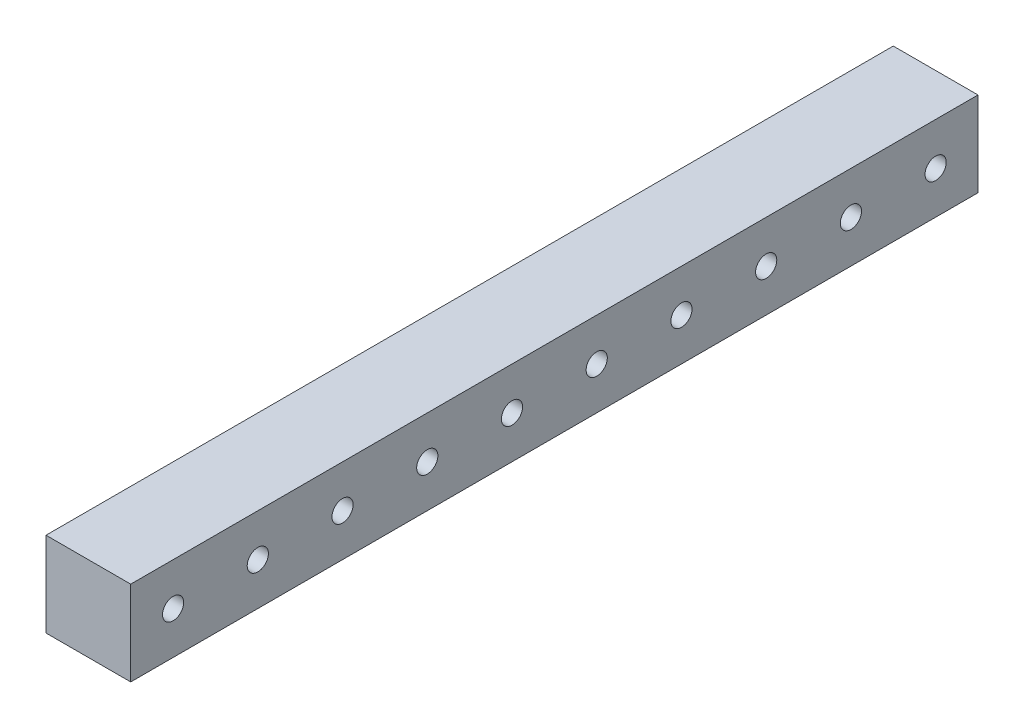
SolidWorks part; units mm, degrees
material "Pine"
ref_plane "Front Plane" through (0, 0, 0) normal (0, 0, 1) x (1, 0, 0)
ref_plane "Top Plane" through (0, 0, 0) normal (0, 1, 0) x (1, 0, 0)
ref_plane "Right Plane" through (0, 0, 0) normal (1, 0, 0) x (0, 0, -1)
sketch "Sketch1" plane through (0, 0, 0) normal (0, 0, 1) x (1, 0, 0)
  line L0 (-10, -10) -> (10, 10) construction
  line L1 (-10, 10) -> (10, 10)
  line L2 (-10, 10) -> (-10, -10)
  line L3 (-10, -10) -> (10, -10)
  line L4 (10, 10) -> (10, -10)
  point P4 (0, 0)
  dimension "D1" = 20
  dimension "D2" = 45
extrude "Boss-Extrude1" add sketch "Sketch1" along normal blind 200
hole_wizard "Ø5.0mm Dowel Hole1" positions "Sketch2" profile "Sketch3" hole size "Ø5.0" standard "ANSI Metric" end condition through all
sketch "Sketch2" plane through (10, 0, 0) normal (1, 0, 0) x (0, 0, -1)
  line L0 (0, -10) -> (0, 10) construction
  point P0 (-10, 0)
  point P7 (0, 0)
  dimension "D1" = 10
sketch "Sketch3" plane through (10, 0, 10) normal (0, 1, 0) x (0, 0, -1)
  line L0 (0, 0) -> (0, 20)
  line L1 (0, 20) -> (2.5, 20)
  line L2 (2.5, 20) -> (2.5, 0)
  line L5 (2.5, 0) -> (0, 0)
  line L11 (0, -6.35) -> (0, 107.95) construction
  dimension "Thru Hole Dia." = 5
  dimension "Thru Hole Depth" = 20
pattern_linear "LPattern2" count 10 spacing 20 along (0, 0, 1) of "Ø5.0mm Dowel Hole1"
